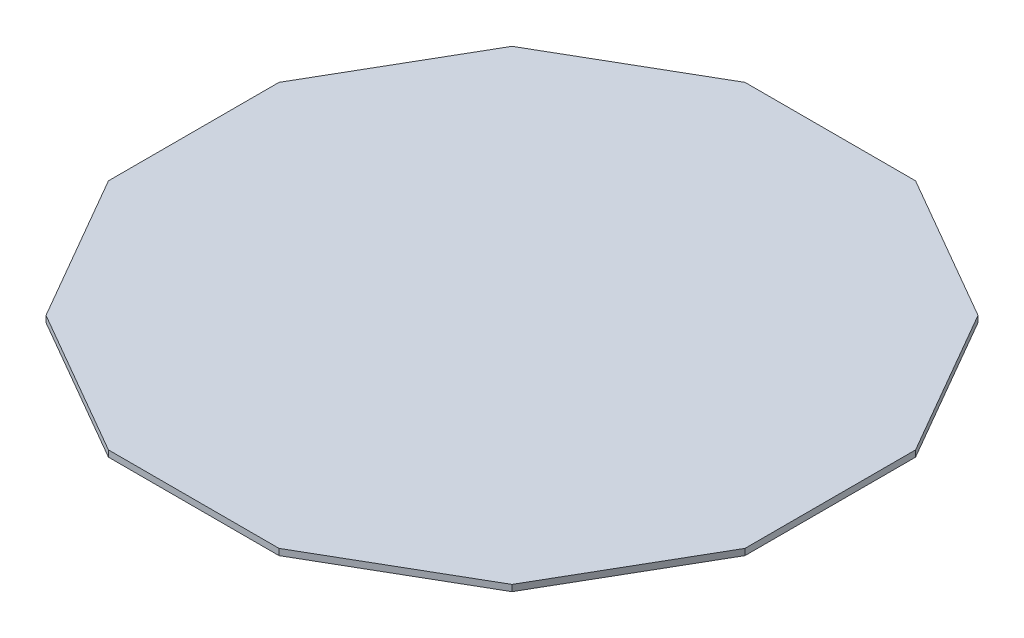
SolidWorks part; units mm, degrees
material "ABS PC"
ref_plane "Front Plane" through (0, 0, 0) normal (0, 0, 1) x (1, 0, 0)
ref_plane "Top Plane" through (0, 0, 0) normal (0, 1, 0) x (1, 0, 0)
ref_plane "Right Plane" through (0, 0, 0) normal (1, 0, 0) x (0, 0, -1)
sketch "Sketch1" plane through (0, 0, 0) normal (0, 1, 0) x (1, 0, 0)
  line L0 (39.444, 147.2071) -> (-39.444, 147.2071)
  line L1 (-39.444, 147.2071) -> (-107.7631, 107.7631)
  line L2 (-107.7631, 107.7631) -> (-147.2071, 39.444)
  line L3 (-147.2071, 39.444) -> (-147.2071, -39.444)
  line L4 (-147.2071, -39.444) -> (-107.7631, -107.7631)
  line L5 (-107.7631, -107.7631) -> (-39.444, -147.2071)
  line L6 (-39.444, -147.2071) -> (39.444, -147.2071)
  line L7 (39.444, -147.2071) -> (107.7631, -107.7631)
  line L8 (107.7631, -107.7631) -> (147.2071, -39.444)
  line L9 (147.2071, -39.444) -> (147.2071, 39.444)
  line L10 (147.2071, 39.444) -> (107.7631, 107.7631)
  line L11 (107.7631, 107.7631) -> (39.444, 147.2071)
  circle A0 centre (0, 0) radius 152.4
  dimension "D1" = 304.8
extrude "Boss-Extrude1" add sketch "Sketch1" against normal blind 2.921 contours L10 L11 L0 L1 L2 L3 L4 L5 L6 L7 L8 L9
